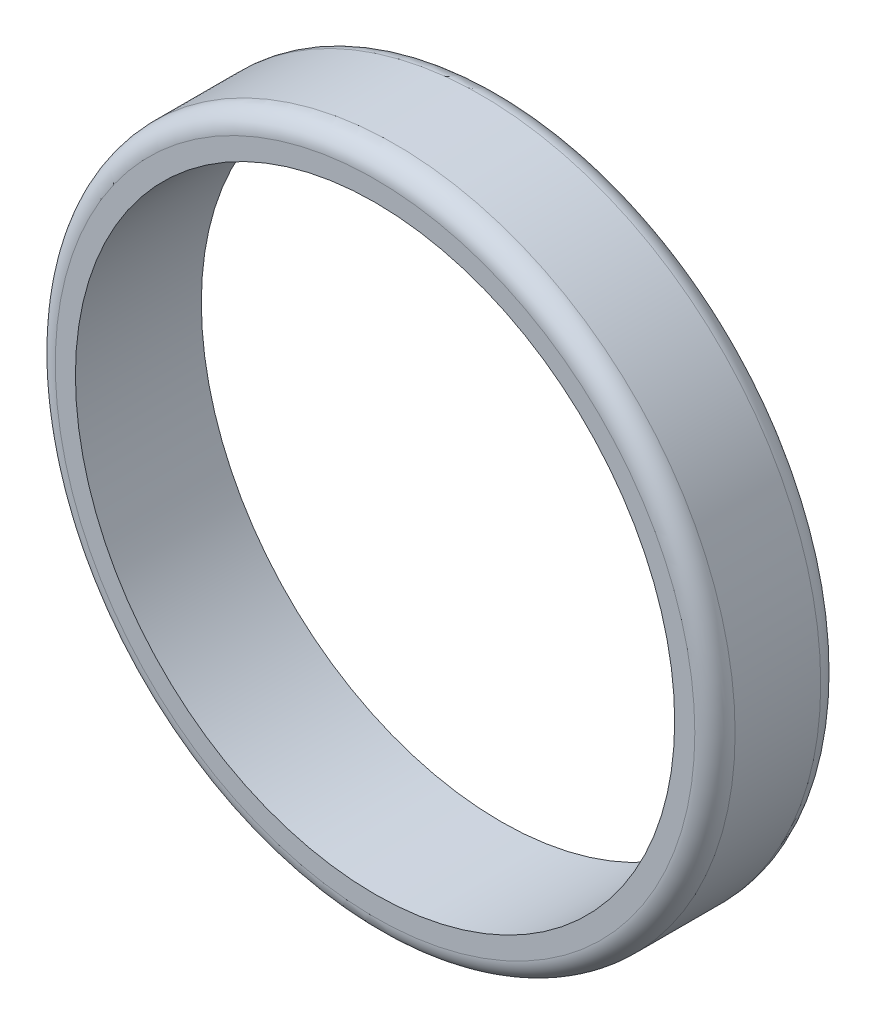
SolidWorks part; units mm, degrees
ref_plane "前视基准面" through (0, 0, 0) normal (0, 0, 1) x (1, 0, 0)
ref_plane "上视基准面" through (0, 0, 0) normal (0, 1, 0) x (1, 0, 0)
ref_plane "右视基准面" through (0, 0, 0) normal (1, 0, 0) x (0, 0, -1)
other "Configuration Table"
sketch "草图1" plane through (0, 0, 0) normal (0, 0, 1) x (1, 0, 0)
  circle A0 centre (0, 0) radius 59.5
  circle A1 centre (0, 0) radius 67.5
  dimension "D1" = 119
  dimension "D2" = 135
extrude "凸台-拉伸1" add sketch "草图1" along normal blind 25
fillet "圆角1" radius 4 2 edges at (67.5, 0, 0) (67.5, 0, 25)
